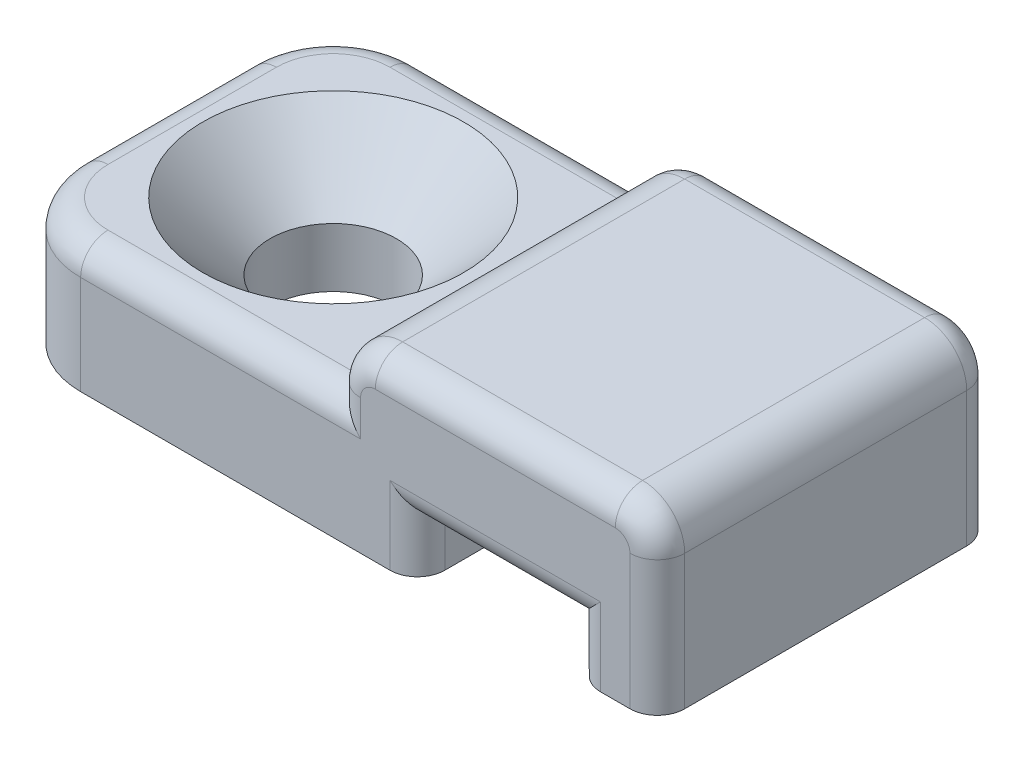
SolidWorks part; units mm, degrees
ref_plane "Plano frontal" through (0, 0, 0) normal (0, 0, 1) x (1, 0, 0)
ref_plane "Plano superior" through (0, 0, 0) normal (0, 1, 0) x (1, 0, 0)
ref_plane "Plano direito" through (0, 0, 0) normal (1, 0, 0) x (0, 0, -1)
sketch "Esboço1" plane through (0, 0, 0) normal (0, 0, 1) x (1, 0, 0)
  line L1 (-11.5, -1.2) -> (-11.5, 1.8)
  line L2 (-11.5, 1.8) -> (-3.5, 1.8)
  line L3 (-3.5, 1.8) -> (-3.5, 3)
  line L4 (-3.5, 3) -> (4.2, 3)
  line L5 (4.2, 3) -> (4.2, -1.2)
  line L7 (-1.5, 0) -> (-1.5, -1.2)
  line L8 (2.2, 0) -> (2.2, -1.2)
  line L9 (-11.5, -1.2) -> (-1.5, -1.2)
  line L10 (-1.5, 0) -> (2.2, 0)
  line L11 (2.2, -1.2) -> (4.2, -1.2)
  dimension "D1" = 2
  dimension "D2" = 1.2
  dimension "D3" = 8
  dimension "D4" = 3.7
  dimension "D5" = 2
  dimension "D6" = 3
  dimension "D8" = 3
extrude "Ressalto-extrusão1" add sketch "Esboço1" along normal blind 8
sketch "Esboço2" plane through (0, 1.8, 0) normal (0, 1, 0) x (1, 0, 0)
  line L0 (-3.5, -8) -> (-11.5, 0) construction
  circle A0 centre (-7.5, -4) radius 1.5
  point P2 (-11.5, 0)
  point P3 (-3.5, -8)
  dimension "D1" = 3
extrude "Corte-extrusão1" cut sketch "Esboço2" against normal blind 6
chamfer "Chanfro2" distance 1.6 angle 45 1 edges at (-9, 1.8, 4)
fillet "Filete3" radius 2 2 edges at (-11.5, 0.3, 8) (-11.5, 0.3, 0)
fillet "Filete5" radius 1 2 edges at (-3.5, 3, 4) (4.2, 3, 4)
fillet "Filete6" radius 0.65 21 edges at (-1.5, -0.6, 8) (2.2, -0.6, 8) (-1.5, -0.6, 0) (2.2, -0.6, 0) (4.2, 0.4, 8) (3.9071, 2.7071, 8) (-3.5, 1.9, 8) (-3.2071, 2.7071, 8) (-6.5, 1.8, 8) (-10.9142, 1.8, 7.4142) (-6.5, 1.8, 0) (-10.9142, 1.8, 0.5858) (4.2, 0.4, 0) (3.9071, 2.7071, 0) (-3.5, 1.9, 0) (-3.2071, 2.7071, 0) (0.35, 0, 8) (0.35, 0, 0) (0.35, 3, 8) (-11.5, 1.8, 4) (0.35, 3, 0)
